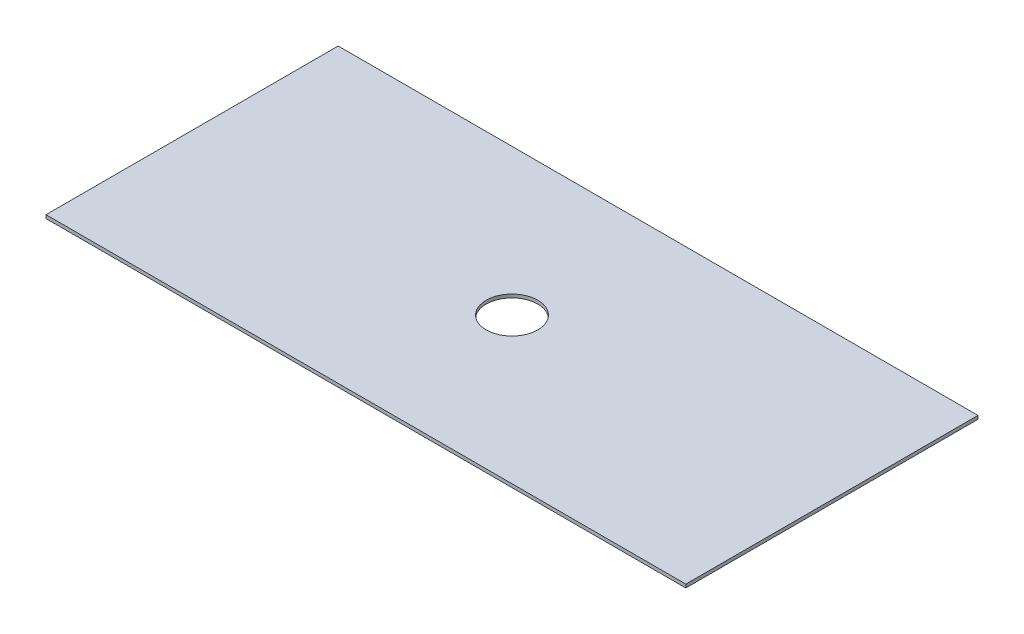
SolidWorks part; units mm, degrees
material "PVC 0.007 Plasticized"
ref_plane "Front Plane" through (0, 0, 0) normal (0, 0, 1) x (1, 0, 0)
ref_plane "Top Plane" through (0, 0, 0) normal (0, 1, 0) x (1, 0, 0)
ref_plane "Right Plane" through (0, 0, 0) normal (1, 0, 0) x (0, 0, -1)
sketch "Sketch1" plane through (0, 0, 0) normal (0, 1, 0) x (1, 0, 0)
  line L1 (473, -216) -> (-473, -216)
  line L2 (473, -216) -> (473, 216)
  line L3 (473, 216) -> (-473, 216)
  line L4 (-473, -216) -> (-473, 216)
  line L5 (473, -216) -> (-473, 216) construction
  line L6 (473, 216) -> (-473, -216) construction
  point P0 (0, 0)
  dimension "D1" = 432
  dimension "D2" = 946
extrude "Boss-Extrude1" add sketch "Sketch1" along normal blind 5
sketch "Sketch2" plane through (0, 0, 0) normal (0, -1, 0) x (-1, 0, 0)
  circle A0 centre (0, 0) radius 38.1
  dimension "D1" = 76.2
extrude "Cut-Extrude1" cut sketch "Sketch2" against normal blind 5
